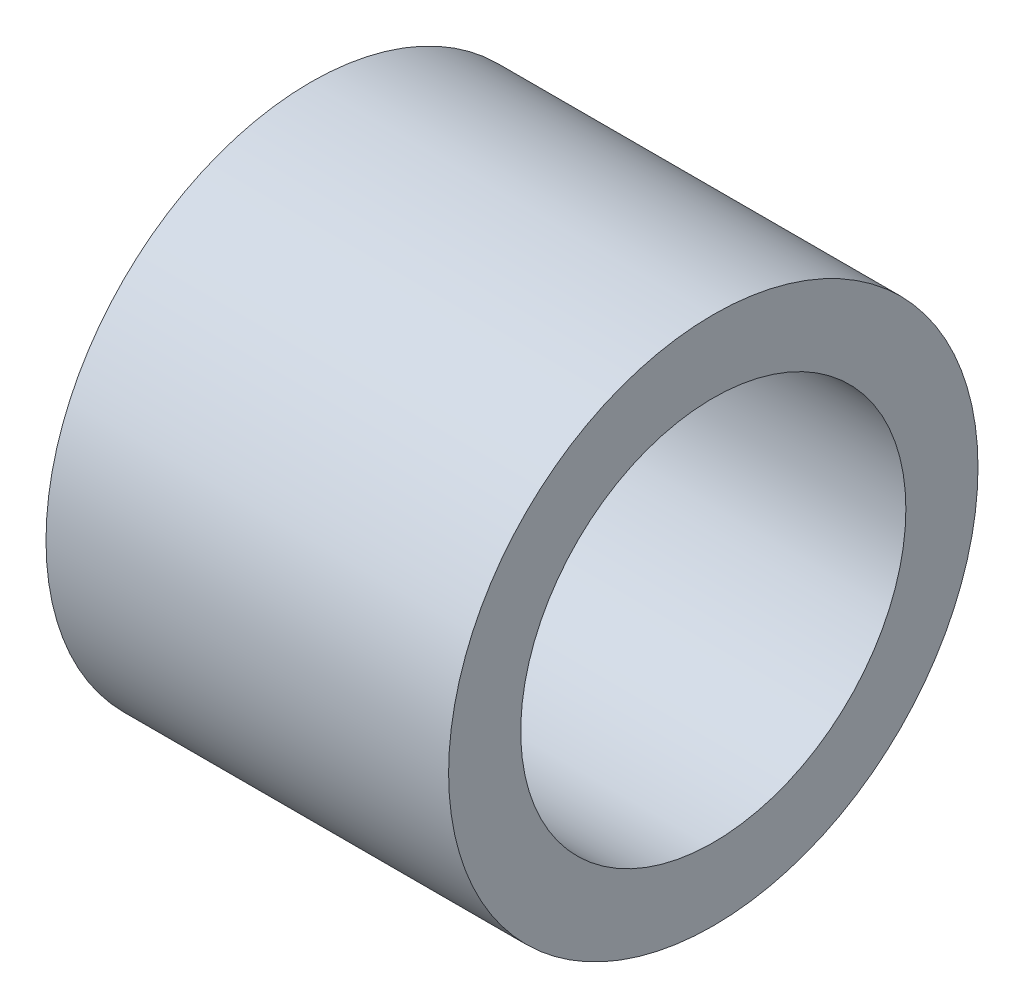
SolidWorks part; units mm, degrees
material "PVC Rígido"
ref_plane "Alzado" through (0, 0, 0) normal (0, 0, 1) x (1, 0, 0)
ref_plane "Planta" through (0, 0, 0) normal (0, 1, 0) x (1, 0, 0)
ref_plane "Vista lateral" through (0, 0, 0) normal (1, 0, 0) x (0, 0, -1)
sketch "Croquis1" plane through (0, 0, 0) normal (1, 0, 0) x (0, 0, -1)
  circle A0 centre (0, 0) radius 16.7
  circle A1 centre (0, 0) radius 12.15
  dimension "D1" = 33.4
  dimension "D2" = 24.3
extrude "Saliente-Extruir1" add sketch "Croquis1" along normal blind 25.4
